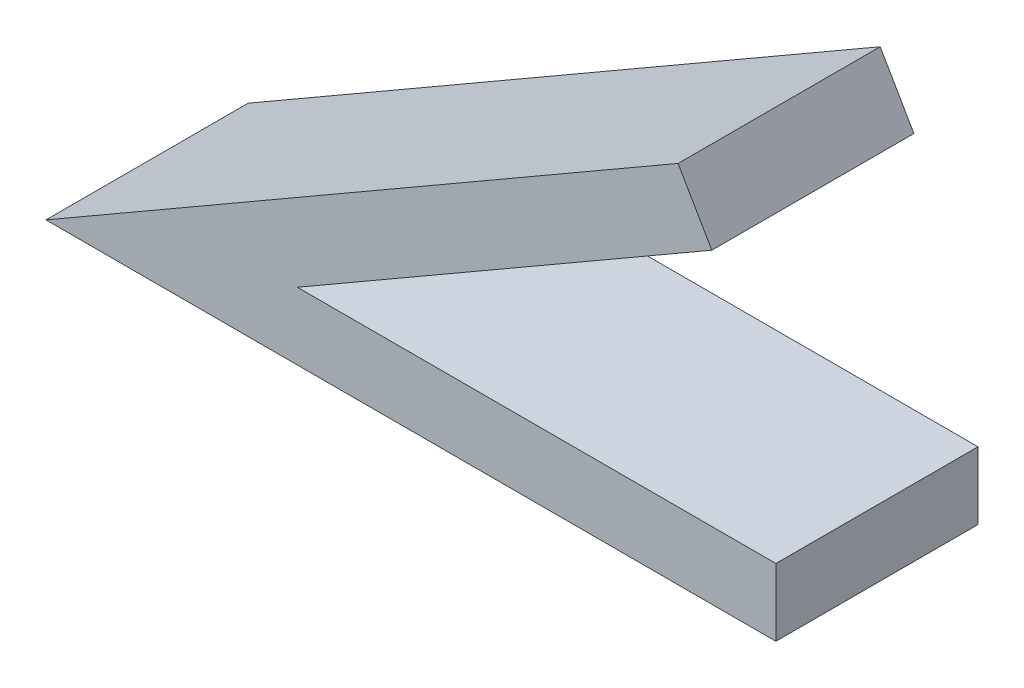
SolidWorks part; units mm, degrees
ref_plane "前视基准面" through (0, 0, 0) normal (0, 0, 1) x (1, 0, 0)
ref_plane "上视基准面" through (0, 0, 0) normal (0, 1, 0) x (1, 0, 0)
ref_plane "右视基准面" through (0, 0, 0) normal (1, 0, 0) x (0, 0, -1)
sketch "草图1" plane through (0, 0, 0) normal (0, 0, 1) x (1, 0, 0)
  line L0 (0, 0) -> (-65, 0)
  line L1 (-65, 0) -> (-8.7083, 32.5)
  line L2 (-8.7083, 32.5) -> (-5.7083, 27.3038)
  line L3 (0, 0) -> (0, 6)
  line L4 (0, 6) -> (-42.6077, 6)
  line L5 (-42.6077, 6) -> (-5.7083, 27.3038)
  dimension "D1" = 65
  dimension "D2" = 65
  dimension "D3" = 30
  dimension "D4" = 6
  dimension "D5" = 6
extrude "凸台-拉伸1" add sketch "草图1" along normal blind 18
